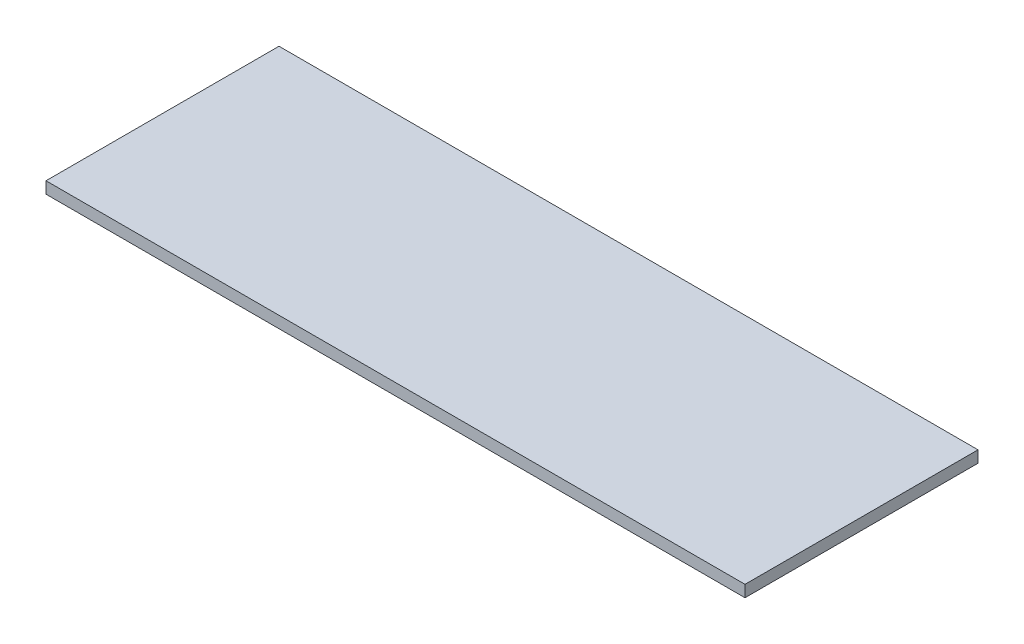
SolidWorks part; units mm, degrees
ref_plane "Front Plane" through (0, 0, 0) normal (0, 0, 1) x (1, 0, 0)
ref_plane "Top Plane" through (0, 0, 0) normal (0, 1, 0) x (1, 0, 0)
ref_plane "Right Plane" through (0, 0, 0) normal (1, 0, 0) x (0, 0, -1)
sketch "Sketch1" plane through (0, 0, 0) normal (0, 1, 0) x (1, 0, 0)
  line L1 (0, 0) -> (300, 0)
  line L2 (0, 0) -> (0, -100)
  line L3 (0, -100) -> (300, -100)
  line L4 (300, 0) -> (300, -100)
extrude "Boss-Extrude1" add sketch "Sketch1" along normal blind 5
